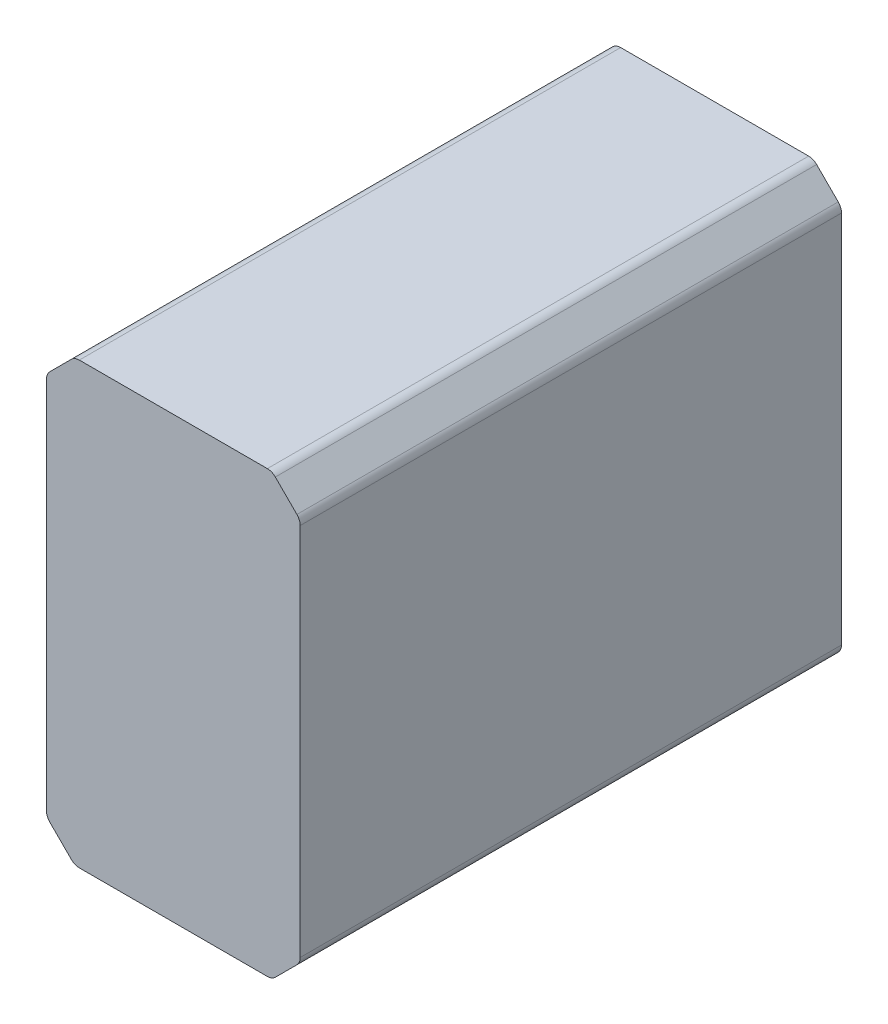
SolidWorks part; units mm, degrees
ref_plane "前视基准面" through (0, 0, 0) normal (0, 0, 1) x (1, 0, 0)
ref_plane "上视基准面" through (0, 0, 0) normal (0, 1, 0) x (1, 0, 0)
ref_plane "右视基准面" through (0, 0, 0) normal (1, 0, 0) x (0, 0, -1)
sketch "草图1" plane through (0, 0, 0) normal (0, 0, 1) x (1, 0, 0)
  line L1 (0, 0) -> (90, 0)
  line L2 (0, 0) -> (0, -156)
  line L3 (0, -156) -> (90, -156)
  line L4 (90, 0) -> (90, -156)
extrude "凸台-拉伸1" add sketch "草图1" along normal blind 192
chamfer "倒角1" distance 10 angle 45 4 edges at (0, -156, 96) (90, -156, 96) (0, 0, 96) (90, 0, 96)
fillet "圆角1" radius 4 8 edges at (10, 0, 96) (0, -10, 96) (10, -156, 96) (0, -146, 96) (80, -156, 96) (90, -146, 96) (90, -10, 96) (80, 0, 96)
